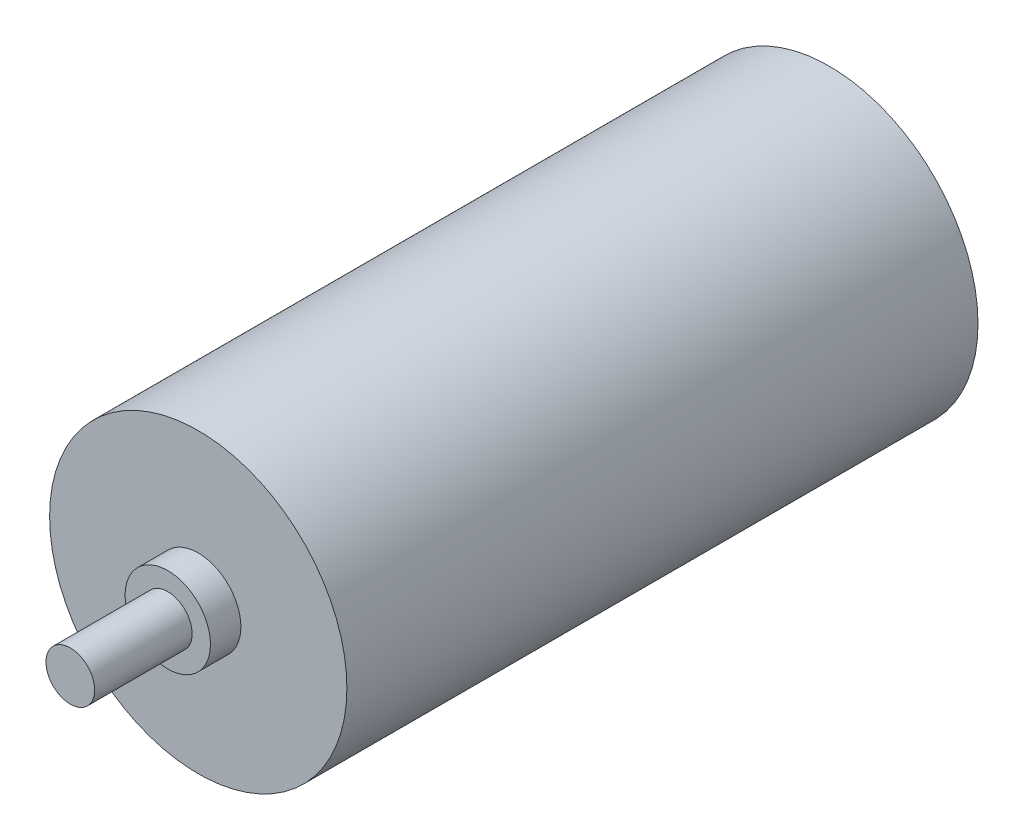
SolidWorks part; units mm, degrees
ref_plane "前视基准面" through (0, 0, 0) normal (0, 0, 1) x (1, 0, 0)
ref_plane "上视基准面" through (0, 0, 0) normal (0, 1, 0) x (1, 0, 0)
ref_plane "右视基准面" through (0, 0, 0) normal (1, 0, 0) x (0, 0, -1)
sketch "草图1" plane through (0, 0, 0) normal (0, 0, 1) x (1, 0, 0)
  circle A0 centre (0, 0) radius 12.2
  dimension "D1" = 24.4
extrude "凸台-拉伸1" add sketch "草图1" along normal blind 51.8 contours A0
sketch "草图5" plane through (0, 0, 51.8) normal (0, 0, 1) x (1, 0, 0)
  circle A0 centre (0, 0) radius 3.5
  dimension "D1" = 7
extrude "凸台-拉伸3" add sketch "草图5" along normal blind 2.5
sketch "草图6" plane through (0, 0, 54.3) normal (0, 0, 1) x (1, 0, 0)
  circle A0 centre (0, 0) radius 2
  dimension "D1" = 4
extrude "凸台-拉伸4" add sketch "草图6" along normal blind 8
sketch "草图8" plane through (0, 0, 0) normal (0, 0, -1) x (-1, 0, 0)
  circle A0 centre (0, 8.5) radius 1.3724
  circle A1 centre (0, -8.5) radius 1.37
  ellipse E0 centre (-8.5, 0) end of major axis (-8.5, -2.6402) minor radius 1.0763
  ellipse E1 centre (8.5, 0) end of major axis (8.5, -2.6402) minor radius 1.0426
  dimension "D3" = 8.5
  dimension "D1" = 8.5
  dimension "D2" = 8.5
  dimension "D4" = 8.5
sketch "草图9" plane through (0, 0, 51.8) normal (0, 0, 1) x (1, 0, 0)
  circle A0 centre (0, 8.5) radius 1.37
sketch "草图10" plane through (0, 0, 51.8) normal (0, 0, 1) x (1, 0, 0)
  line L0 (0, -13.42) -> (0, 13.42) construction
  circle A0 centre (0, -8.5) radius 1.37
  circle A1 centre (0, 0) radius 12.2 construction
